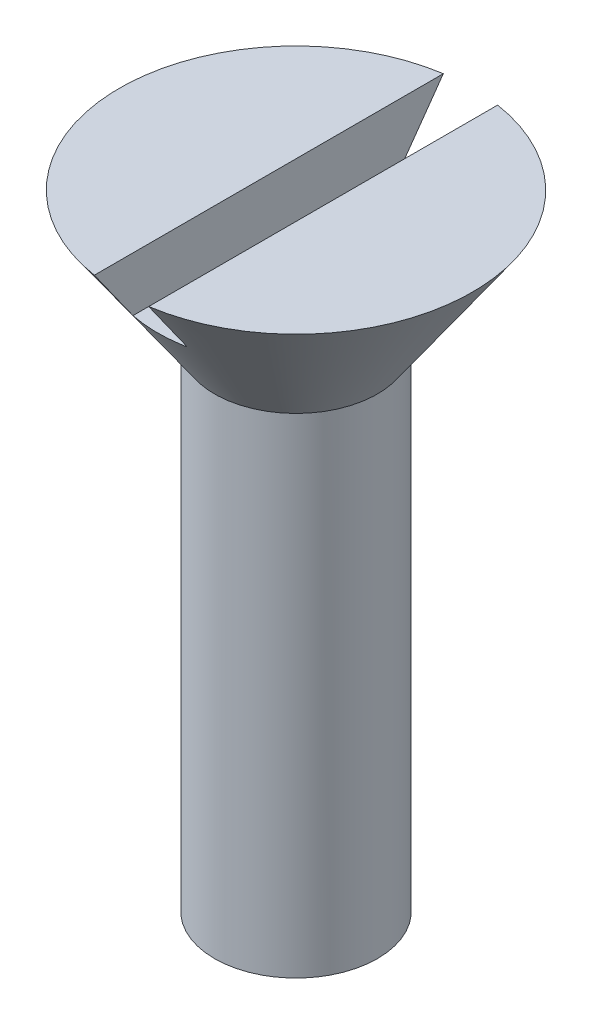
SolidWorks part; units mm, degrees
ref_plane "Front Plane" through (0, 0, 0) normal (0, 0, 1) x (1, 0, 0)
ref_plane "Top Plane" through (0, 0, 0) normal (0, 1, 0) x (1, 0, 0)
ref_plane "Right Plane" through (0, 0, 0) normal (1, 0, 0) x (0, 0, -1)
sketch "Sketch1" plane through (0, 0, 0) normal (0, 0, 1) x (1, 0, 0)
  line L0 (0, -7.7715) -> (6.5, -7.7715)
  line L1 (6.5, -7.7715) -> (3, -12.7715)
  line L2 (3, -12.7715) -> (3, -30.7715)
  line L3 (3, -30.7715) -> (0, -32.5035)
  line L4 (0, -32.5035) -> (0, -7.7715)
  dimension "D1" = 6.5
revolve "Revolve1" add sketch "Sketch1" angle 360 about L4
sketch "Sketch3" plane through (0, 0, 0) normal (0, 0, 1) x (1, 0, 0)
  line L0 (6.5, -7.7715) -> (-6.5, -7.7715) construction
  line L1 (1, -7.7715) -> (-1, -7.7715)
  line L2 (1, -7.7715) -> (1, -9.7715)
  line L3 (1, -9.7715) -> (-1, -9.7715)
  line L4 (-1, -7.7715) -> (-1, -9.7715)
  dimension "D1" = 2
  dimension "D2" = 2
  dimension "D3" = 0
  dimension "D4" = 5.5
  dimension "D5" = 5.5
  dimension "D6" = 2
  dimension "D7" = 2
sketch "Sketch4" plane through (0, 0, 0) normal (0, 0, 1) x (1, 0, 0)
  line L1 (1, -7.7715) -> (-1, -7.7715)
  line L2 (1, -7.7715) -> (1, -9.7715)
  line L3 (1, -9.7715) -> (-1, -9.7715)
  line L4 (-1, -7.7715) -> (-1, -9.7715)
extrude "Cut-Extrude1" cut sketch "Sketch4" against normal blind 11 and the other way blind 12
